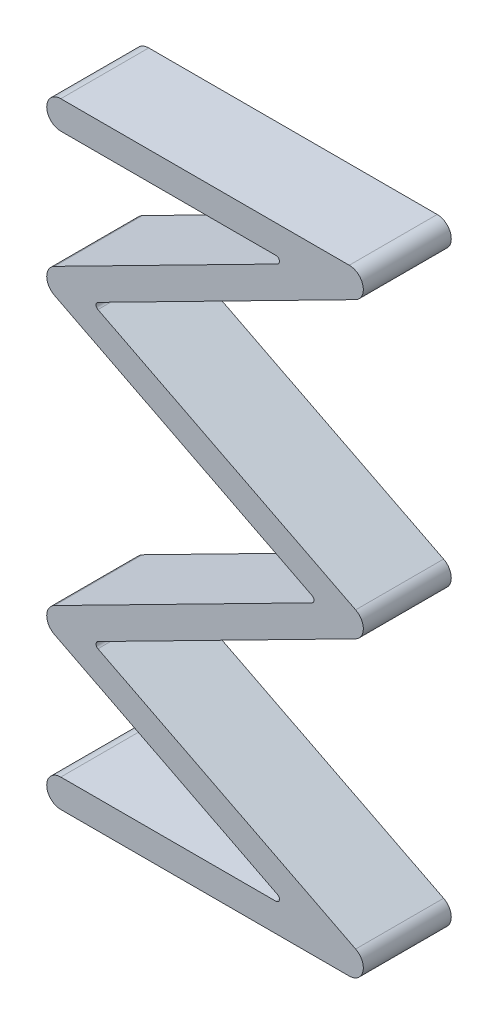
SolidWorks part; units mm, degrees
ref_plane "Front Plane" through (0, 0, 0) normal (0, 0, 1) x (1, 0, 0)
ref_plane "Top Plane" through (0, 0, 0) normal (0, 1, 0) x (1, 0, 0)
ref_plane "Right Plane" through (0, 0, 0) normal (1, 0, 0) x (0, 0, -1)
sketch "Sketch2" plane through (0, 0, 0) normal (0, 0, 1) x (1, 0, 0)
  line L0 (0.4, 0.4) -> (8.6, 0.4) construction
  line L1 (0, 0) -> (9, 0) construction
  line L2 (0, 0) -> (0, 17.5) construction
  line L3 (0, 17.5) -> (9, 17.5) construction
  line L4 (9, 0) -> (9, 17.5) construction
  line L5 (0.4, 17.1) -> (8.6, 17.1) construction
  line L6 (8.6, 17.1) -> (0.4, 12.925) construction
  line L7 (0.4, 12.925) -> (8.6, 8.75) construction
  line L8 (8.6, 8.75) -> (0.4, 4.575) construction
  line L9 (0.4, 4.575) -> (8.6, 0.4) construction
  line L10 (0.4, 16.7) -> (6.9328, 16.7)
  line L11 (6.9328, 16.7) -> (-0.4816, 12.925)
  line L12 (-0.4816, 12.925) -> (7.7184, 8.75)
  line L13 (7.7184, 8.75) -> (-0.4816, 4.575)
  line L14 (-0.4816, 4.575) -> (6.9328, 0.8)
  line L15 (0.4, 0.8) -> (6.9328, 0.8)
  line L16 (0.4, 17.5) -> (10.2672, 17.5)
  line L17 (10.2672, 17.5) -> (1.2816, 12.925)
  line L18 (1.2816, 12.925) -> (9.4816, 8.75)
  line L19 (9.4816, 8.75) -> (1.2816, 4.575)
  line L20 (1.2816, 4.575) -> (10.2672, 0)
  line L21 (0.4, 0) -> (10.2672, 0)
  line L22 (0.4, 4.575) -> (1.2816, 4.575) construction
  arc A0 (0.4, 16.7) -> (0.4, 17.5) centre (0.4, 17.1) cw
  arc A1 (0.4, 0.8) -> (0.4, 0) centre (0.4, 0.4) ccw
  point P9 (9.6, 8.5)
  dimension "D1" = 17.5
  dimension "D2" = 9
  dimension "D3" = 0.4
  dimension "D4" = 0.4
  dimension "D5" = 0.4
  dimension "D7" = 0.4
  dimension "D8" = 0.4
  dimension "D9" = 0.4
extrude "Boss-Extrude1" add sketch "Sketch2" along normal blind 2.5
fillet "Fillet1" radius 0.4 5 edges at (10.2672, 0, 1.25) (9.4816, 8.75, 1.25) (10.2672, 17.5, 1.25) (-0.4816, 12.925, 1.25) (-0.4816, 4.575, 1.25)
fillet "Fillet2" radius 0.1 5 edges at (6.9328, 0.8, 1.25) (1.2816, 4.575, 1.25) (1.2816, 12.925, 1.25) (7.7184, 8.75, 1.25) (6.9328, 16.7, 1.25)
